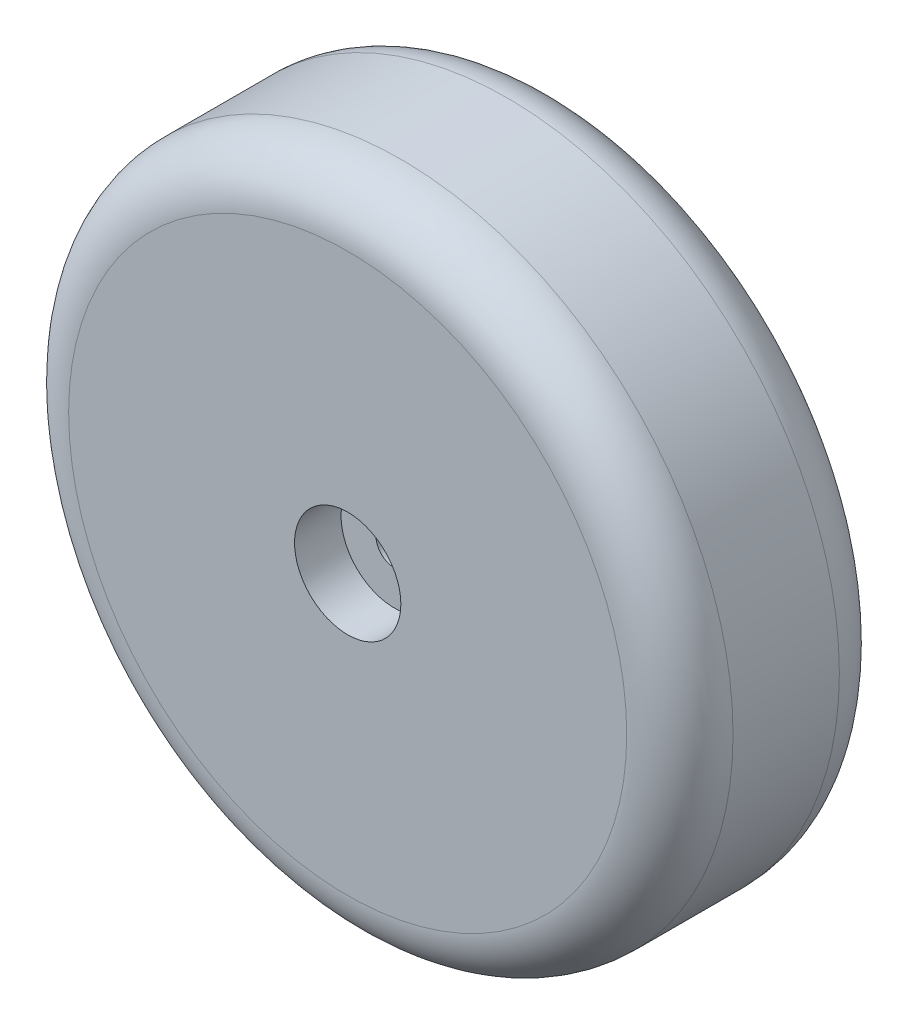
SolidWorks part; units mm, degrees
ref_plane "前视基准面" through (0, 0, 0) normal (0, 0, 1) x (1, 0, 0)
ref_plane "上视基准面" through (0, 0, 0) normal (0, 1, 0) x (1, 0, 0)
ref_plane "右视基准面" through (0, 0, 0) normal (1, 0, 0) x (0, 0, -1)
other "质心 (COM)"
sketch "草图1" plane through (0, 0, 0) normal (0, 0, 1) x (1, 0, 0)
  circle A0 centre (0, 0) radius 50
  dimension "D1" = 100
extrude "凸台-拉伸1" add sketch "草图1" along normal blind 32
sketch "草图2" plane through (0, 0, 32) normal (0, 0, 1) x (1, 0, 0)
  circle A0 centre (0, 0) radius 2.75
  dimension "D1" = 5.5
extrude "切除-拉伸1" cut sketch "草图2" against normal through all
fillet "圆角1" radius 8 2 edges at (50, 0, 0) (50, 0, 32)
sketch "草图3" plane through (0, 0, 32) normal (0, 0, 1) x (1, 0, 0)
  circle A0 centre (0, 0) radius 8
  dimension "D1" = 16
extrude "切除-拉伸2" cut sketch "草图3" against normal blind 7
sketch "草图4" plane through (0, 0, 0) normal (0, 0, -1) x (-1, 0, 0)
  circle A0 centre (0, 0) radius 8
  dimension "D1" = 16
extrude "切除-拉伸3" cut sketch "草图4" against normal blind 7
